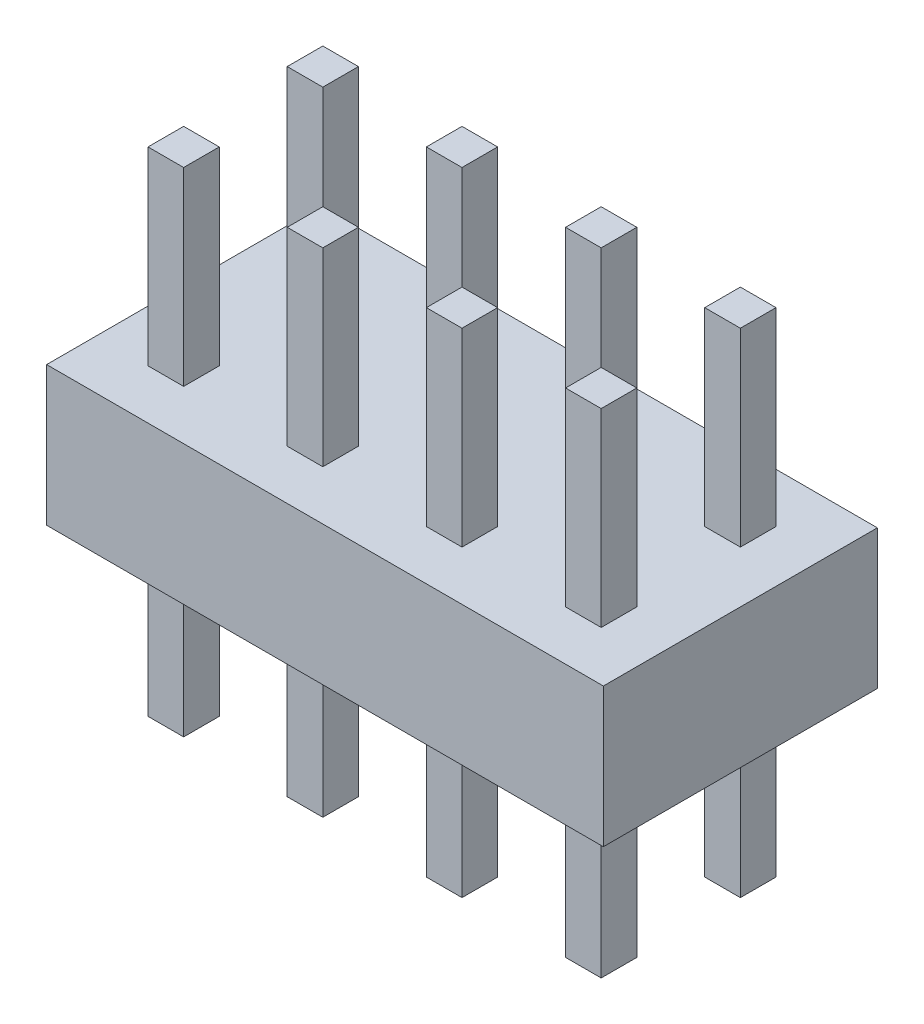
SolidWorks part; units mm, degrees
ref_plane "Front Plane" through (0, 0, 0) normal (0, 0, 1) x (1, 0, 0)
ref_plane "Top Plane" through (0, 0, 0) normal (0, 1, 0) x (1, 0, 0)
ref_plane "Right Plane" through (0, 0, 0) normal (1, 0, 0) x (0, 0, -1)
sketch "Sketch1" plane through (0, 0, 0) normal (0, 1, 0) x (1, 0, 0)
  line L0 (1.27, 1.23) -> (1.27, 3.77) construction
  line L1 (0, 0) -> (10.16, 0)
  line L2 (0, 0) -> (0, 5)
  line L3 (0, 5) -> (10.16, 5)
  line L4 (10.16, 0) -> (10.16, 5)
  line L9 (0.945, 3.445) -> (1.595, 3.445)
  line L10 (0.945, 3.445) -> (0.945, 4.095)
  line L11 (0.945, 4.095) -> (1.595, 4.095)
  line L12 (1.595, 3.445) -> (1.595, 4.095)
  line L13 (0.945, 3.445) -> (1.595, 4.095) construction
  line L14 (0.945, 4.095) -> (1.595, 3.445) construction
  line L15 (0.945, 1.555) -> (1.595, 1.555)
  line L16 (0.945, 1.555) -> (0.945, 0.905)
  line L17 (0.945, 0.905) -> (1.595, 0.905)
  line L18 (1.595, 1.555) -> (1.595, 0.905)
  line L19 (0.945, 1.555) -> (1.595, 0.905) construction
  line L20 (0.945, 0.905) -> (1.595, 1.555) construction
  line L21 (3.485, 3.445) -> (3.485, 4.095)
  line L22 (3.485, 3.445) -> (4.135, 3.445)
  line L23 (4.135, 3.445) -> (4.135, 4.095)
  line L24 (3.485, 4.095) -> (4.135, 4.095)
  line L25 (6.025, 3.445) -> (6.025, 4.095)
  line L26 (6.025, 3.445) -> (6.675, 3.445)
  line L27 (6.675, 3.445) -> (6.675, 4.095)
  line L28 (6.025, 4.095) -> (6.675, 4.095)
  line L29 (8.565, 3.445) -> (8.565, 4.095)
  line L30 (8.565, 3.445) -> (9.215, 3.445)
  line L31 (9.215, 3.445) -> (9.215, 4.095)
  line L32 (8.565, 4.095) -> (9.215, 4.095)
  line L33 (3.81, 3.445) -> (3.81, 4.4838) construction
  line L34 (3.485, 1.555) -> (3.485, 0.905)
  line L35 (3.485, 1.555) -> (4.135, 1.555)
  line L36 (4.135, 1.555) -> (4.135, 0.905)
  line L37 (3.485, 0.905) -> (4.135, 0.905)
  line L38 (6.025, 1.555) -> (6.025, 0.905)
  line L39 (6.025, 1.555) -> (6.675, 1.555)
  line L40 (6.675, 1.555) -> (6.675, 0.905)
  line L41 (6.025, 0.905) -> (6.675, 0.905)
  line L42 (8.565, 1.555) -> (8.565, 0.905)
  line L43 (8.565, 1.555) -> (9.215, 1.555)
  line L44 (9.215, 1.555) -> (9.215, 0.905)
  line L45 (8.565, 0.905) -> (9.215, 0.905)
  point P5 (1.27, 3.77)
  point P10 (1.27, 1.23)
  point P15 (0, 2.5)
  point P18 (1.27, 2.5)
  point P32 (3.81, 3.445)
  point P34 (3.81, 1.555)
  dimension "D1" = 10.16
  dimension "D2" = 5
  dimension "D3" = 0.65
  dimension "D4" = 0.65
  dimension "D5" = 0.65
  dimension "D6" = 0.65
  dimension "D7" = 2.54
  dimension "D8" = 1.27
  dimension "D10" = 2.54
  dimension "D9" = 4
  dimension "D11" = 4
extrude "Boss-Extrude1" add sketch "Sketch1" along normal blind 2.54
ref_plane "Plane1" through (0, -3, 0) normal (0, -1, 0) x (-1, 0, 0)
sketch "Sketch2" plane through (0, -3, 0) normal (0, -1, 0) x (-1, 0, 0)
  line L0 (-8.89, 1.23) -> (-8.89, 3.77) construction
  line L5 (-9.215, 3.445) -> (-8.565, 3.445)
  line L6 (-9.215, 3.445) -> (-9.215, 4.095)
  line L7 (-9.215, 4.095) -> (-8.565, 4.095)
  line L8 (-8.565, 3.445) -> (-8.565, 4.095)
  line L9 (-9.215, 3.445) -> (-8.565, 4.095) construction
  line L10 (-9.215, 4.095) -> (-8.565, 3.445) construction
  line L11 (-9.215, 1.555) -> (-8.565, 1.555)
  line L12 (-9.215, 1.555) -> (-9.215, 0.905)
  line L13 (-9.215, 0.905) -> (-8.565, 0.905)
  line L14 (-8.565, 1.555) -> (-8.565, 0.905)
  line L15 (-9.215, 1.555) -> (-8.565, 0.905) construction
  line L16 (-9.215, 0.905) -> (-8.565, 1.555) construction
  line L41 (-10.16, 0) -> (-10.16, 5) construction
  line L43 (-10.16, 5) -> (-10.16, 0)
  line L44 (-6.675, 3.445) -> (-6.025, 3.445)
  line L45 (-6.025, 3.445) -> (-6.025, 4.095)
  line L46 (-6.675, 4.095) -> (-6.025, 4.095)
  line L47 (-6.675, 3.445) -> (-6.675, 4.095)
  line L48 (-4.135, 3.445) -> (-3.485, 3.445)
  line L49 (-3.485, 3.445) -> (-3.485, 4.095)
  line L50 (-4.135, 4.095) -> (-3.485, 4.095)
  line L51 (-4.135, 3.445) -> (-4.135, 4.095)
  line L52 (-1.595, 3.445) -> (-0.945, 3.445)
  line L53 (-0.945, 3.445) -> (-0.945, 4.095)
  line L54 (-1.595, 4.095) -> (-0.945, 4.095)
  line L55 (-1.595, 3.445) -> (-1.595, 4.095)
  line L56 (-6.35, 3.445) -> (-6.35, 5.1319) construction
  line L57 (-6.675, 1.555) -> (-6.025, 1.555)
  line L58 (-6.025, 1.555) -> (-6.025, 0.905)
  line L59 (-6.675, 0.905) -> (-6.025, 0.905)
  line L60 (-6.675, 1.555) -> (-6.675, 0.905)
  line L61 (-4.135, 1.555) -> (-3.485, 1.555)
  line L62 (-3.485, 1.555) -> (-3.485, 0.905)
  line L63 (-4.135, 0.905) -> (-3.485, 0.905)
  line L64 (-4.135, 1.555) -> (-4.135, 0.905)
  line L65 (-1.595, 1.555) -> (-0.945, 1.555)
  line L66 (-0.945, 1.555) -> (-0.945, 0.905)
  line L67 (-1.595, 0.905) -> (-0.945, 0.905)
  line L68 (-1.595, 1.555) -> (-1.595, 0.905)
  point P4 (-8.89, 3.77)
  point P9 (-8.89, 1.23)
  point P14 (-10.16, 2.5)
  point P17 (-8.89, 2.5)
  point P33 (-6.35, 3.445)
  point P36 (-6.35, 0.905)
  dimension "D1" = 1.27
  dimension "D2" = 4
  dimension "D3" = 0.65
  dimension "D4" = 0.65
  dimension "D5" = 0.65
  dimension "D6" = 0.65
  dimension "D7" = 2.54
  dimension "D8" = 2.54
  dimension "D9" = 4
extrude "Boss-Extrude2" add sketch "Sketch2" against normal blind 9 contours L5 L8 L7 L6 | L57 L60 L59 L58 | L47 L44 L45 L46 | L61 L64 L63 L62 | L51 L48 L49 L50 | L65 L68 L67 L66 | L14 L13 L12 L11 | L55 L54 L53 L52
